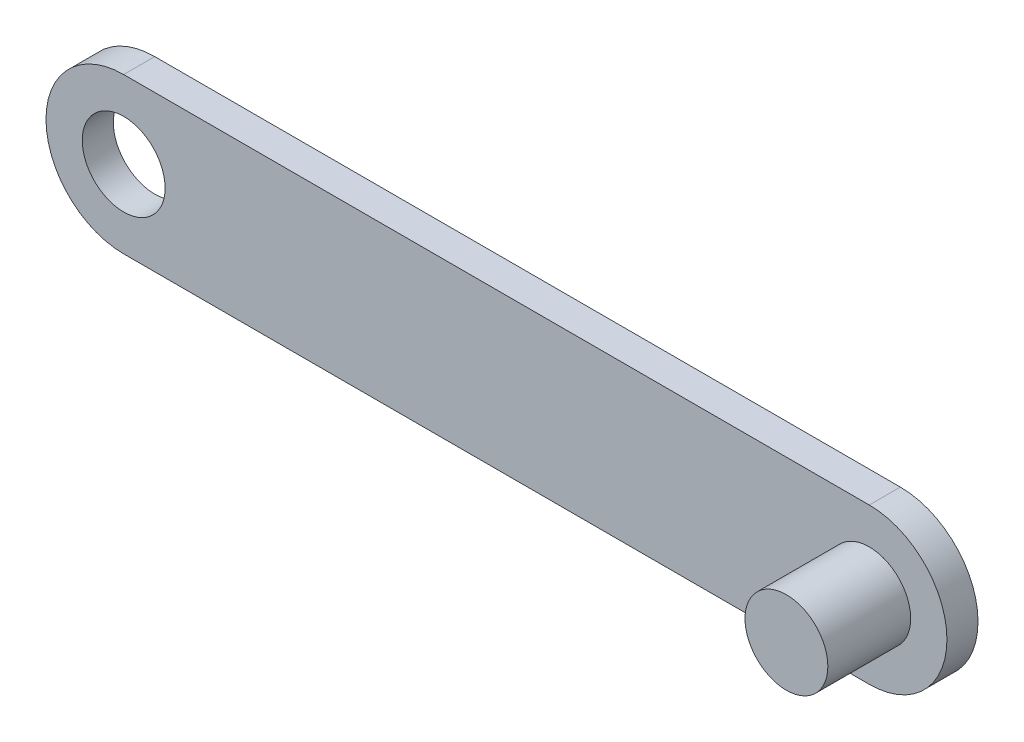
SolidWorks part; units mm, degrees
material "PBT General Purpose"
ref_plane "Front Plane" through (0, 0, 0) normal (0, 0, 1) x (1, 0, 0)
ref_plane "Top Plane" through (0, 0, 0) normal (0, 1, 0) x (1, 0, 0)
ref_plane "Right Plane" through (0, 0, 0) normal (1, 0, 0) x (0, 0, -1)
sketch "Sketch1" plane through (0, 0, 0) normal (0, 0, 1) x (1, 0, 0)
  line L0 (0, 7.5) -> (72, 7.5)
  line L6 (0, -7.5) -> (72, -7.5)
  arc A2 (0, 7.5) -> (0, -7.5) centre (0, 0) ccw
  arc A3 (72, -7.5) -> (72, 7.5) centre (72, 0) ccw
  dimension "D1" = 15
  dimension "D2" = 72
extrude "Boss-Extrude4" add sketch "Sketch1" along normal blind 3
sketch "Sketch4" plane through (0, 0, 3) normal (0, 0, 1) x (1, 0, 0)
  circle A0 centre (0, 0) radius 4
  dimension "D1" = 8
extrude "Cut-Extrude1" cut sketch "Sketch4" against normal through all
sketch "Sketch5" plane through (0, 0, 3) normal (0, 0, 1) x (1, 0, 0)
  circle A0 centre (72, 0) radius 4
  arc A3 (72, -7.5) -> (72, 7.5) centre (72, 0) ccw construction
  dimension "D1" = 8
extrude "Boss-Extrude5" add sketch "Sketch5" along normal blind 8
